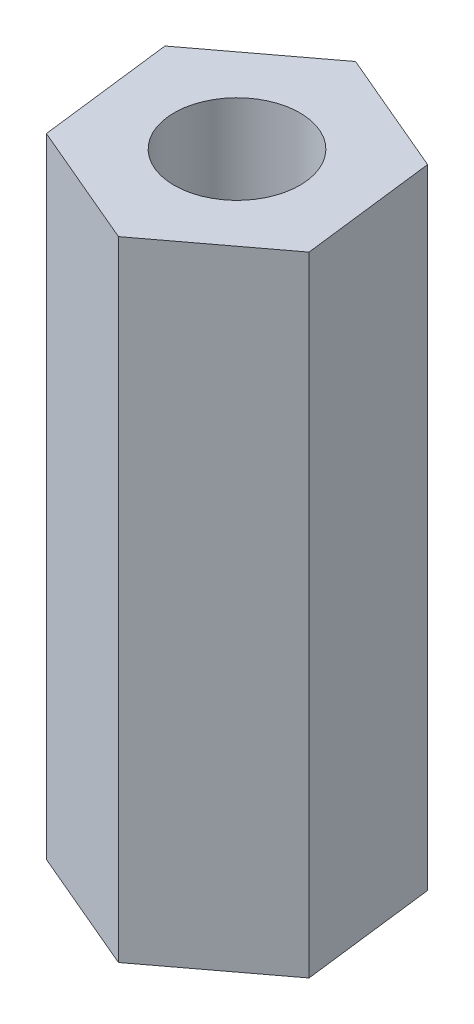
SolidWorks part; units mm, degrees
material "黄铜"
ref_plane "前视基准面" through (0, 0, 0) normal (0, 0, 1) x (1, 0, 0)
ref_plane "上视基准面" through (0, 0, 0) normal (0, 1, 0) x (1, 0, 0)
ref_plane "右视基准面" through (0, 0, 0) normal (1, 0, 0) x (0, 0, -1)
sketch "草图1" plane through (0, 0, 0) normal (0, 1, 0) x (1, 0, 0)
  line L1 (2.7672, 2.0839) -> (-0.4211, 3.4384)
  line L2 (-0.4211, 3.4384) -> (-3.1883, 1.3545)
  line L3 (-3.1883, 1.3545) -> (-2.7672, -2.0839)
  line L4 (-2.7672, -2.0839) -> (0.4211, -3.4384)
  line L5 (0.4211, -3.4384) -> (3.1883, -1.3545)
  line L6 (3.1883, -1.3545) -> (2.7672, 2.0839)
  circle A0 centre (0, 0) radius 1.6
  circle A1 centre (0, 0) radius 3 construction
  dimension "D1" = 3.2
extrude "凸台-拉伸1" add sketch "草图1" along normal blind 16
